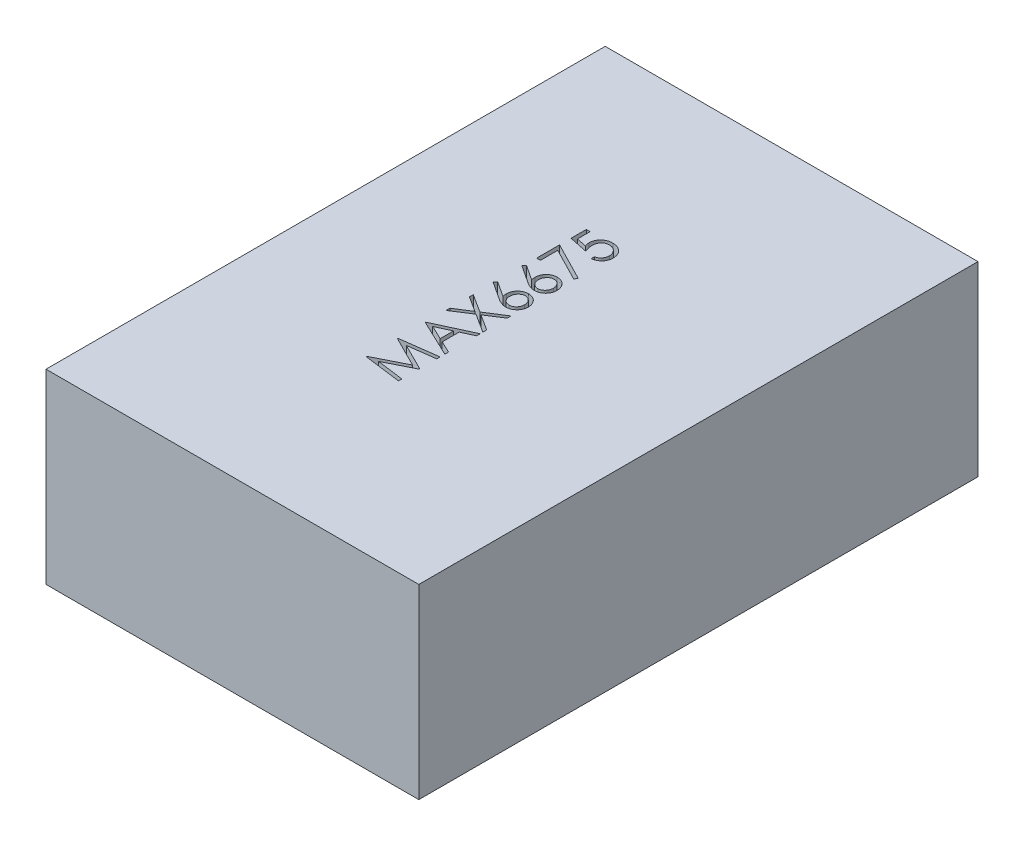
SolidWorks part; units mm, degrees
ref_plane "Front Plane" through (0, 0, 0) normal (0, 0, 1) x (1, 0, 0)
ref_plane "Top Plane" through (0, 0, 0) normal (0, 1, 0) x (1, 0, 0)
ref_plane "Right Plane" through (0, 0, 0) normal (1, 0, 0) x (0, 0, -1)
sketch "Sketch1" plane through (0, 0, 0) normal (0, 1, 0) x (1, 0, 0)
  line L1 (-10, 15) -> (10, 15)
  line L2 (-10, 15) -> (-10, -15)
  line L3 (-10, -15) -> (10, -15)
  line L4 (10, 15) -> (10, -15)
  line L5 (-10, 15) -> (10, -15) construction
  line L6 (-10, -15) -> (10, 15) construction
  point P0 (0, 0)
  dimension "D1" = 20
  dimension "D2" = 30
extrude "Boss-Extrude1" add sketch "Sketch1" along normal blind 10
sketch "Sketch2" plane through (0, 10, 0) normal (0, 1, 0) x (1, 0, 0)
  line L0 (0, -15) -> (0, 15) construction
  line L1 (-10, -15) -> (10, -15) construction
  line L2 (10, 15) -> (-10, 15) construction
  text T0 "MAX6675" font "Century Gothic" height 2
extrude "Cut-Extrude1" cut sketch "Sketch2" against normal blind 2
